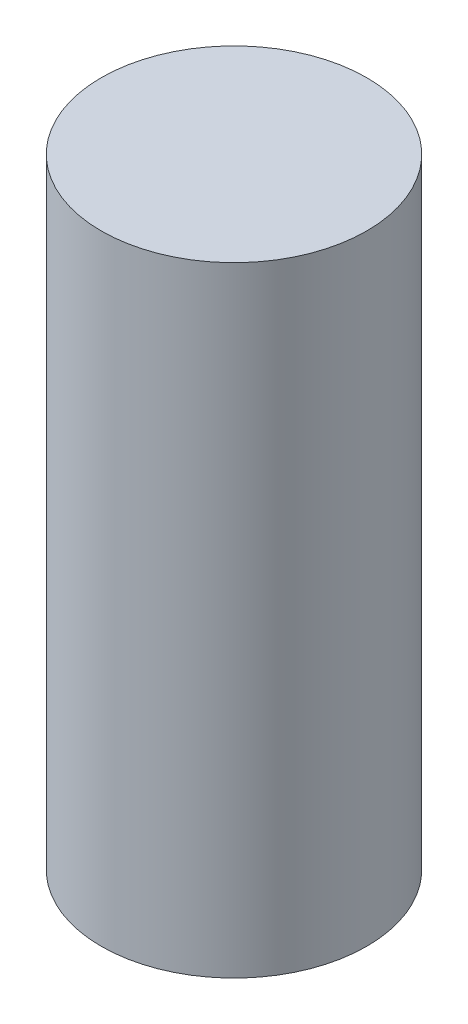
SolidWorks part; units mm, degrees
ref_plane "Front Plane" through (0, 0, 0) normal (0, 0, 1) x (1, 0, 0)
ref_plane "Top Plane" through (0, 0, 0) normal (0, 1, 0) x (1, 0, 0)
ref_plane "Right Plane" through (0, 0, 0) normal (1, 0, 0) x (0, 0, -1)
other "Configuration Table"
sketch "Sketch1" plane through (0, 0, 0) normal (0, 1, 0) x (1, 0, 0)
  circle A0 centre (650, 770) radius 6
extrude "PACK_ayar_mil_4" add sketch "Sketch1" along normal blind 28 from offset 12 separate body
